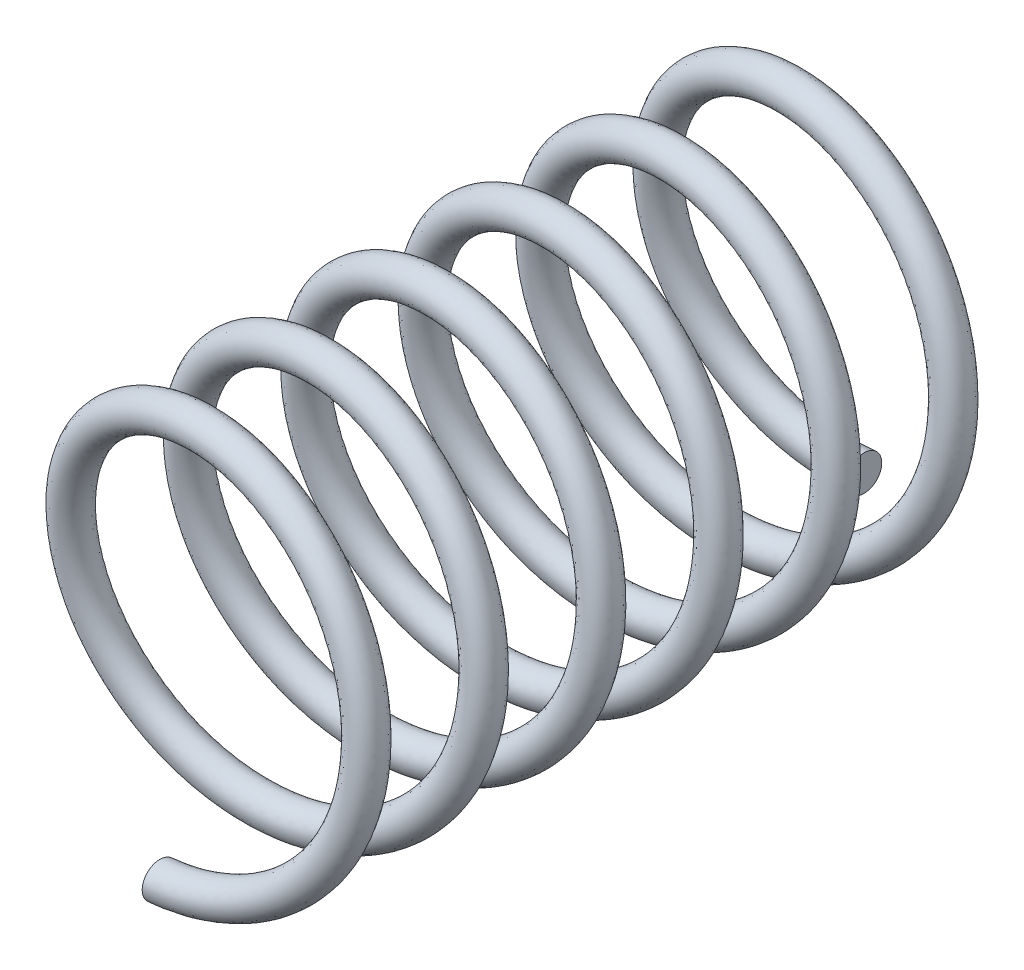
SolidWorks part; units mm, degrees
ref_plane "Front Plane" through (0, 0, 0) normal (0, 0, 1) x (1, 0, 0)
ref_plane "Top Plane" through (0, 0, 0) normal (0, 1, 0) x (1, 0, 0)
ref_plane "Right Plane" through (0, 0, 0) normal (1, 0, 0) x (0, 0, -1)
sketch "Sketch2" plane through (0, 0, 0) normal (0, 1, 0) x (1, 0, 0)
  circle A0 centre (3.7936, 0) radius 0.3479
sketch "Sketch3" plane through (0, 0, 0) normal (0, 0, 1) x (1, 0, 0)
  circle A0 centre (0, 0) radius 3
  dimension "D1" = 6
curve "Helix/Spiral2" pitch 2 height 12 turns 6
sketch "Sketch4" plane through (0, 0, 0) normal (1, 0, 0) x (0, 0, -1)
  circle A0 centre (0, -3) radius 0.3
  dimension "D1" = 0.6
  dimension "D2" = 3
sweep "Sweep1" add profiles "Sketch4" path "Helix/Spiral2"
